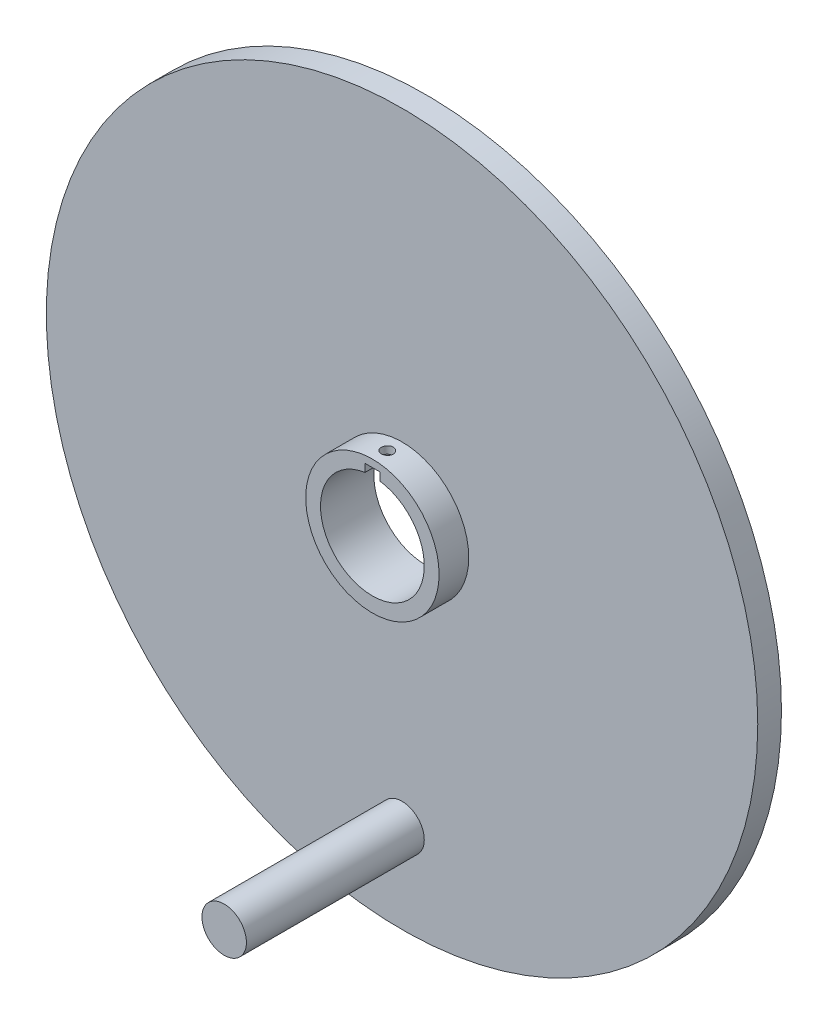
SolidWorks part; units mm, degrees
ref_plane "Front" through (0, 0, 0) normal (0, 0, 1) x (1, 0, 0)
ref_plane "Top" through (0, 0, 0) normal (0, 1, 0) x (1, 0, 0)
ref_plane "Right" through (0, 0, 0) normal (1, 0, 0) x (0, 0, -1)
sketch "Sketch1" plane through (0, 0, 0) normal (0, 0, 1) x (1, 0, 0)
  line L1 (-2.5, 20) -> (2.5, 20)
  line L2 (-2.5, 20) -> (-2.5, 17.3205)
  line L4 (2.5, 20) -> (2.5, 17.3205)
  circle A0 centre (0, 0) radius 120
  arc A1 (-2.5, 17.3205) -> (2.5, 17.3205) centre (0, 0) ccw
  point P4 (0, 17.5)
  point P9 (0, 20)
  dimension "D1" = 240
  dimension "D2" = 35
  dimension "D3" = 2.5
extrude "Boss-Extrude1" add sketch "Sketch1" along normal blind 8
sketch "Sketch2" plane through (0, 0, 8) normal (0, 0, 1) x (1, 0, 0)
  line L0 (-2.5, 17.3205) -> (-2.5, 20)
  line L1 (-2.5, 20) -> (2.5, 20)
  line L2 (2.5, 20) -> (2.5, 17.3205)
  circle A0 centre (0, 0) radius 22.5
  arc A1 (-2.5, 17.3205) -> (2.5, 17.3205) centre (0, 0) ccw
  dimension "D1" = 45
extrude "Boss-Extrude2" add sketch "Sketch2" along normal blind 10
sketch "Sketch3" plane through (0, 0, 0) normal (0, 1, 0) x (1, 0, 0)
  line L0 (0, -8) -> (0, -18) construction
  line L1 (-22.5, -8) -> (22.5, -8) construction
  line L2 (-22.5, -18) -> (22.5, -18) construction
  circle A0 centre (0, -13) radius 2
  dimension "D1" = 4
extrude "Cut-Extrude1" cut sketch "Sketch3" along normal blind 25
sketch "Sketch4" plane through (0, 0, 8) normal (0, 0, 1) x (1, 0, 0)
  line L0 (0, 0) -> (0, -90) construction
  circle A0 centre (0, -90) radius 7.5
  dimension "D2" = 15
  dimension "D1" = 90
extrude "Boss-Extrude3" add sketch "Sketch4" along normal blind 60
ref_plane "Plane1" through (0, 0, 4) normal (0, 0, -1) x (-1, 0, 0)
